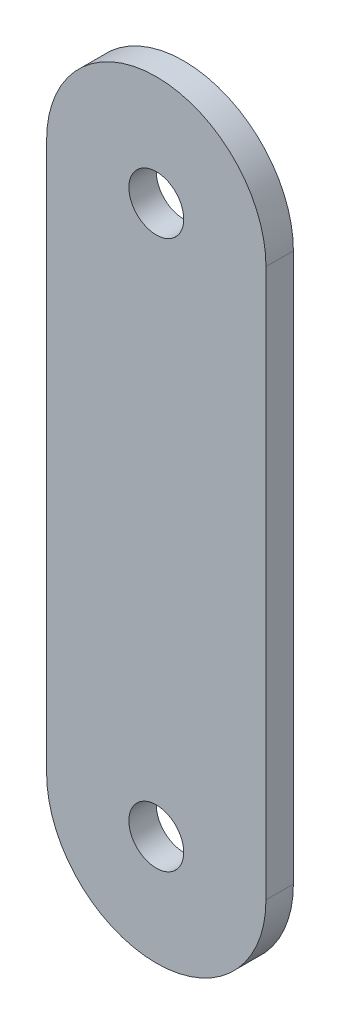
SolidWorks part; units mm, degrees
material "5052-H32"
ref_plane "Front Plane" through (0, 0, 0) normal (0, 0, 1) x (1, 0, 0)
ref_plane "Top Plane" through (0, 0, 0) normal (0, 1, 0) x (1, 0, 0)
ref_plane "Right Plane" through (0, 0, 0) normal (1, 0, 0) x (0, 0, -1)
sketch "Sketch1" plane through (0, 0, 0) normal (0, 0, 1) x (1, 0, 0)
  line L0 (-50.8, -254) -> (-50.8, 0)
  line L1 (50.8, 0) -> (50.8, -254)
  arc A0 (50.8, 0) -> (-50.8, 0) centre (0, 0) ccw
  arc A1 (-50.8, -254) -> (50.8, -254) centre (0, -254) ccw
  circle A2 centre (0, 0) radius 12.7
  circle A3 centre (0, -254) radius 12.7
  dimension "D1" = 50.8
  dimension "D3" = 25.4
  dimension "D4" = 25.4
  dimension "D2" = 254
extrude "Boss-Extrude1" add sketch "Sketch1" along normal blind 12.7
sketch "Sketch2" plane through (0, 0, 0) normal (0, 0, -1) x (-1, 0, 0)
  line L0 (-605.189, 2050.457) -> (-44.5223, 2050.457) construction
